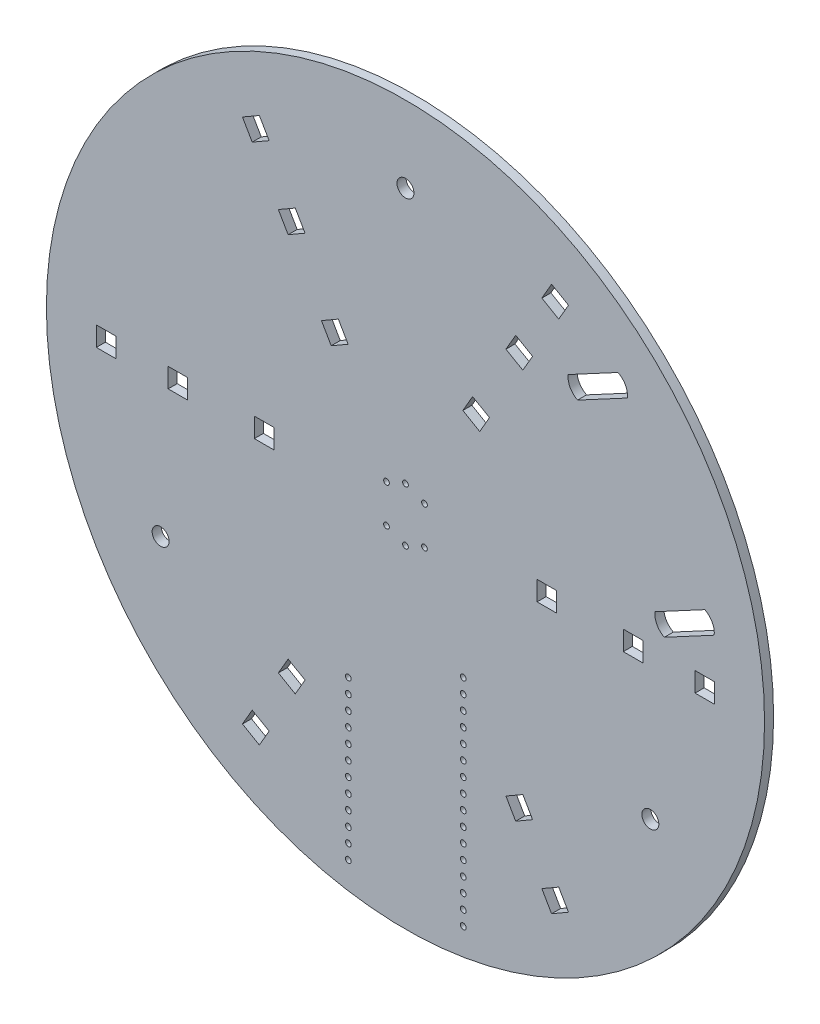
SolidWorks part; units mm, degrees
ref_plane "Front Plane" through (0, 0, 0) normal (0, 0, 1) x (1, 0, 0)
ref_plane "Top Plane" through (0, 0, 0) normal (0, 1, 0) x (1, 0, 0)
ref_plane "Right Plane" through (0, 0, 0) normal (1, 0, 0) x (0, 0, -1)
sketch "Sketch1" plane through (0, 0, 0) normal (0, 0, 1) x (1, 0, 0)
  circle A0 centre (0, 0) radius 63.5
  dimension "D1" = 127
extrude "Boss-Extrude1" add sketch "Sketch1" along normal blind 1.6
sketch "Sketch2" plane through (0, 0, 0) normal (0, 0, -1) x (-1, 0, 0)
  circle A0 centre (0, 0) radius 50
  circle A1 centre (0, 50) radius 1.5
  circle A2 centre (43.3013, -25) radius 1.5
  circle A3 centre (-43.3013, -25) radius 1.5
  point P11 (0, 0)
  dimension "D1" = 100
  dimension "D2" = 3
  dimension "D3" = 3
sketch "Sketch3" plane through (0, 0, 0) normal (0, 0, -1) x (-1, 0, 0)
  circle A0 centre (-34.0063, 36.6548) radius 1.75
  circle A1 centre (-49.3547, 8.0073) radius 1.75
  circle A2 centre (0, 0) radius 63.5 construction
  dimension "D1" = 3.5
  dimension "D2" = 3.5
  dimension "D3" = 32.5
  dimension "D4" = 50
  dimension "D5" = 50
extrude "Cut-Extrude4" cut sketch "Sketch3" against normal blind 1.6
extrude "Cut-Extrude5" cut sketch "Sketch2" against normal blind 1.6 contours A1 | A3 | A2
sketch "Sketch4" plane through (0, 0, 0) normal (0, 0, -1) x (-1, 0, 0)
  line L0 (-34.8328, 35.1122) -> (-48.5282, 9.5498) construction
  line L2 (-52.9355, 11.9111) -> (-44.1209, 7.1886)
  line L3 (-54.5884, 8.826) -> (-45.7738, 4.1034)
  line L6 (-39.2401, 37.4735) -> (-30.4255, 32.7509)
  line L7 (-37.5872, 40.5586) -> (-28.7726, 35.836)
  arc A1 (-45.7738, 4.1034) -> (-44.1209, 7.1886) centre (-47.151, 6.8266) ccw
  circle A2 centre (-34.0063, 36.6548) radius 1.75 construction
  arc A3 (-30.4255, 32.7509) -> (-28.7726, 35.836) centre (-31.8027, 35.4741) ccw
  arc A4 (-39.2401, 37.4735) -> (-37.5872, 40.5586) centre (-36.21, 37.8354) cw
  arc A5 (-54.5884, 8.826) -> (-52.9355, 11.9111) centre (-51.5583, 9.1879) cw
  dimension "D3" = 5
extrude "Cut-Extrude6" cut sketch "Sketch4" against normal blind 10 contours L2 A1 L3 A5 | L6 A3 L7 A4
sketch "Sketch5" plane through (0, 0, 0) normal (0, 0, -1) x (-1, 0, 0)
  line L1 (51.215, 1.725) -> (54.665, -1.725) construction
  line L2 (0, -25) -> (0, 0) construction
  line L3 (51.215, -1.725) -> (54.665, 1.725) construction
  line L4 (-14.8564, 22.282) -> (-11.8686, 24.007)
  line L5 (-23.275, -1.725) -> (-26.725, -1.725)
  line L6 (-23.275, -1.725) -> (-23.275, 1.725)
  line L7 (-23.275, 1.725) -> (-26.725, 1.725)
  line L8 (-26.725, -1.725) -> (-26.725, 1.725)
  line L9 (-23.275, -1.725) -> (-26.725, 1.725) construction
  line L10 (-23.275, 1.725) -> (-26.725, -1.725) construction
  line L11 (-38.515, -1.725) -> (-41.965, -1.725)
  line L12 (-38.515, -1.725) -> (-38.515, 1.725)
  line L13 (-38.515, 1.725) -> (-41.965, 1.725)
  line L14 (-41.965, -1.725) -> (-41.965, 1.725)
  line L15 (-38.515, -1.725) -> (-41.965, 1.725) construction
  line L16 (-38.515, 1.725) -> (-41.965, -1.725) construction
  line L17 (-51.215, -1.725) -> (-54.665, -1.725)
  line L18 (-51.215, -1.725) -> (-51.215, 1.725)
  line L19 (-51.215, 1.725) -> (-54.665, 1.725)
  line L20 (-54.665, -1.725) -> (-54.665, 1.725)
  line L21 (-51.215, -1.725) -> (-54.665, 1.725) construction
  line L22 (-51.215, 1.725) -> (-54.665, -1.725) construction
  line L23 (-10.1436, 21.0192) -> (-11.8686, 24.007)
  line L24 (-13.1314, 19.2942) -> (-14.8564, 22.282)
  line L25 (-13.1314, 19.2942) -> (-10.1436, 21.0192)
  line L26 (-22.4764, 35.4803) -> (-19.4886, 37.2053)
  line L27 (-17.7636, 34.2175) -> (-19.4886, 37.2053)
  line L28 (-20.7514, 32.4925) -> (-17.7636, 34.2175)
  line L29 (-20.7514, 32.4925) -> (-22.4764, 35.4803)
  line L30 (-28.8264, 46.4788) -> (-25.8386, 48.2038)
  line L31 (-27.1014, 43.491) -> (-28.8264, 46.4788)
  line L32 (-24.1136, 45.216) -> (-25.8386, 48.2038)
  line L33 (-27.1014, 43.491) -> (-24.1136, 45.216)
  line L34 (11.8686, 24.007) -> (14.8564, 22.282)
  line L35 (13.1314, 19.2942) -> (14.8564, 22.282)
  line L36 (10.1436, 21.0192) -> (11.8686, 24.007)
  line L37 (10.1436, 21.0192) -> (13.1314, 19.2942)
  line L38 (19.4886, 37.2053) -> (22.4764, 35.4803)
  line L39 (20.7514, 32.4925) -> (22.4764, 35.4803)
  line L40 (17.7636, 34.2175) -> (20.7514, 32.4925)
  line L41 (17.7636, 34.2175) -> (19.4886, 37.2053)
  line L42 (25.8386, 48.2038) -> (28.8264, 46.4788)
  line L43 (24.1136, 45.216) -> (25.8386, 48.2038)
  line L44 (27.1014, 43.491) -> (28.8264, 46.4788)
  line L45 (24.1136, 45.216) -> (27.1014, 43.491)
  line L46 (26.725, 1.725) -> (26.725, -1.725)
  line L47 (23.275, -1.725) -> (26.725, -1.725)
  line L48 (23.275, 1.725) -> (26.725, 1.725)
  line L49 (23.275, 1.725) -> (23.275, -1.725)
  line L50 (41.965, 1.725) -> (41.965, -1.725)
  line L51 (38.515, -1.725) -> (41.965, -1.725)
  line L52 (38.515, 1.725) -> (38.515, -1.725)
  line L53 (38.515, 1.725) -> (41.965, 1.725)
  line L54 (54.665, 1.725) -> (54.665, -1.725)
  line L55 (51.215, 1.725) -> (54.665, 1.725)
  line L56 (51.215, -1.725) -> (54.665, -1.725)
  line L57 (51.215, 1.725) -> (51.215, -1.725)
  line L62 (22.4764, -35.4803) -> (19.4886, -37.2053)
  line L63 (17.7636, -34.2175) -> (19.4886, -37.2053)
  line L64 (20.7514, -32.4925) -> (17.7636, -34.2175)
  line L65 (20.7514, -32.4925) -> (22.4764, -35.4803)
  line L66 (28.8264, -46.4788) -> (25.8386, -48.2038)
  line L67 (27.1014, -43.491) -> (28.8264, -46.4788)
  line L68 (24.1136, -45.216) -> (25.8386, -48.2038)
  line L69 (27.1014, -43.491) -> (24.1136, -45.216)
  line L74 (-19.4886, -37.2053) -> (-22.4764, -35.4803)
  line L75 (-20.7514, -32.4925) -> (-22.4764, -35.4803)
  line L76 (-17.7636, -34.2175) -> (-20.7514, -32.4925)
  line L77 (-17.7636, -34.2175) -> (-19.4886, -37.2053)
  line L78 (-25.8386, -48.2038) -> (-28.8264, -46.4788)
  line L79 (-24.1136, -45.216) -> (-25.8386, -48.2038)
  line L80 (-27.1014, -43.491) -> (-28.8264, -46.4788)
  line L81 (-24.1136, -45.216) -> (-27.1014, -43.491)
  line L83 (26.6205, -46.108) -> (27.7715, -44.6516) construction
  line L89 (-28.8264, 46.4788) -> (-24.1136, 45.216) construction
  line L90 (-27.1014, 43.491) -> (-25.8386, 48.2038) construction
  line L91 (-22.4764, 35.4803) -> (-17.7636, 34.2175) construction
  line L92 (-19.4886, 37.2053) -> (-20.7514, 32.4925) construction
  line L93 (-14.8564, 22.282) -> (-10.1436, 21.0192) construction
  line L94 (-11.8686, 24.007) -> (-13.1314, 19.2942) construction
  line L95 (41.965, 1.725) -> (38.515, -1.725) construction
  line L96 (38.515, 1.725) -> (41.965, -1.725) construction
  line L97 (23.275, 1.725) -> (26.725, -1.725) construction
  line L98 (26.725, 1.725) -> (23.275, -1.725) construction
  line L99 (19.4886, 37.2053) -> (20.7514, 32.4925) construction
  line L100 (22.4764, 35.4803) -> (17.7636, 34.2175) construction
  line L101 (25.8386, 48.2038) -> (27.1014, 43.491) construction
  line L102 (24.1136, 45.216) -> (28.8264, 46.4788) construction
  line L103 (11.8686, 24.007) -> (13.1314, 19.2942) construction
  line L104 (10.1436, 21.0192) -> (14.8564, 22.282) construction
  line L109 (-20.7514, -32.4925) -> (-19.4886, -37.2053) construction
  line L110 (-22.4764, -35.4803) -> (-17.7636, -34.2175) construction
  line L111 (-27.1014, -43.491) -> (-25.8386, -48.2038) construction
  line L112 (-28.8264, -46.4788) -> (-24.1136, -45.216) construction
  line L115 (20.7514, -32.4925) -> (19.4886, -37.2053) construction
  line L116 (17.7636, -34.2175) -> (22.4764, -35.4803) construction
  line L117 (27.1014, -43.491) -> (25.8386, -48.2038) construction
  line L118 (24.1136, -45.216) -> (28.8264, -46.4788) construction
  line L119 (-11.8686, -24.007) -> (-14.8564, -22.282) [skipped]
  line L120 (-13.1314, -19.2942) -> (-14.8564, -22.282) [skipped]
  line L121 (-10.1436, -21.0192) -> (-10.4712, -21.5867) [skipped]
  line L122 (-10.1436, -21.0192) -> (-10.5669, -20.7749) [skipped]
  line L123 (10.1436, -21.0192) -> (11.8686, -24.007) [skipped]
  line L124 (14.8564, -22.282) -> (13.3625, -23.1445) [skipped]
  line L125 (13.1314, -19.2942) -> (11.6375, -20.1567) [skipped]
  line L126 (13.1314, -19.2942) -> (14.8564, -22.282) [skipped]
  circle A7 centre (-10.2194, -19.8355) radius 0.508
  circle A8 centre (-10.2194, -22.3755) radius 0.508
  circle A9 centre (-10.2194, -24.9155) radius 0.508
  circle A10 centre (-10.2194, -27.4555) radius 0.508
  circle A11 centre (-10.2194, -29.9955) radius 0.508
  circle A12 centre (-10.2194, -32.5355) radius 0.508
  circle A13 centre (-10.2194, -35.0755) radius 0.508
  circle A14 centre (-10.2194, -37.6155) radius 0.508
  circle A15 centre (-10.2194, -40.1555) radius 0.508
  circle A16 centre (-10.2194, -42.6955) radius 0.508
  circle A17 centre (-10.2194, -45.2355) radius 0.508
  circle A18 centre (-10.2194, -47.7755) radius 0.508
  circle A19 centre (-10.2194, -50.3155) radius 0.508
  circle A20 centre (-10.2194, -52.8555) radius 0.508
  circle A21 centre (-10.2194, -55.3955) radius 0.508
  circle A22 centre (-10.2194, -57.9355) radius 0.508
  circle A23 centre (10.1006, -57.9355) radius 0.508
  circle A24 centre (10.1006, -55.3955) radius 0.508
  circle A25 centre (10.1006, -52.8555) radius 0.508
  circle A26 centre (10.1006, -50.3155) radius 0.508
  circle A27 centre (10.1006, -47.7755) radius 0.508
  circle A28 centre (10.1006, -45.2355) radius 0.508
  circle A29 centre (10.1006, -42.6955) radius 0.508
  circle A30 centre (10.1006, -40.1555) radius 0.508
  circle A31 centre (10.1006, -37.6155) radius 0.508
  circle A32 centre (10.1006, -29.9955) radius 0.508
  circle A33 centre (10.1006, -32.5355) radius 0.508
  circle A34 centre (10.1006, -35.0755) radius 0.508
  point P4 (-25, 0)
  point P11 (-40.24, 0)
  point P89 (0, 0)
  dimension "D10" = 25
  dimension "D2" = 15.24
  dimension "D3" = 25
  dimension "D4" = 2.54
  dimension "D5" = 38.1
  dimension "D7" = 22.7185
  dimension "D8" = 20.32
  dimension "D9" = 19.8355
  dimension "D11" = 0
  dimension "D15" = 15
  dimension "D16" = 2
  dimension "D6" = 6
extrude "Cut-Extrude7" cut sketch "Sketch5" against normal blind 10
sketch "Sketch6" plane through (0, 0, 0) normal (0, 0, -1) x (-1, 0, 0)
  circle A2 centre (0, 4.75) radius 0.5
  circle A3 centre (-3.3588, 3.3588) radius 0.5
  circle A4 centre (3.3588, 3.3588) radius 0.5
  circle A5 centre (3.3588, -3.3588) radius 0.5
  circle A6 centre (0, -4.75) radius 0.5
  circle A7 centre (-3.3588, -3.3588) radius 0.5
  dimension "D2" = 1
extrude "Cut-Extrude8" cut sketch "Sketch6" against normal blind 10
sketch "Sketch7" plane through (0, 0, 0) normal (0, 0, -1) x (-1, 0, 0)
  line L0 (-54.665, 1.725) -> (-51.215, -1.725) construction
  line L1 (-51.215, -1.725) -> (-51.215, 1.725) construction
  line L2 (-51.215, 1.725) -> (-54.665, -1.725) construction
  line L3 (-41.965, 1.725) -> (-38.515, -1.725) construction
  line L4 (-38.515, -1.725) -> (-38.515, 1.725) construction
  line L5 (-38.515, 1.725) -> (-41.965, -1.725) construction
  line L6 (-26.725, 1.725) -> (-23.275, -1.725) construction
  line L7 (-23.275, -1.725) -> (-23.275, 1.725) construction
  line L8 (-23.275, 1.725) -> (-26.725, -1.725) construction
  line L9 (-24.1136, 45.216) -> (-28.8264, 46.4788) construction
  line L10 (-25.8386, 48.2038) -> (-27.1014, 43.491) construction
  line L11 (-19.4886, 37.2053) -> (-20.7514, 32.4925) construction
  line L12 (-17.7636, 34.2175) -> (-22.4764, 35.4803) construction
  line L13 (-11.8686, 24.007) -> (-13.1314, 19.2942) construction
  line L14 (-10.1436, 21.0192) -> (-14.8564, 22.282) construction
  line L15 (27.1014, 43.491) -> (25.8386, 48.2038) construction
  line L16 (28.8264, 46.4788) -> (24.1136, 45.216) construction
  line L17 (22.4764, 35.4803) -> (17.7636, 34.2175) construction
  line L18 (20.7514, 32.4925) -> (19.4886, 37.2053) construction
  line L19 (14.8564, 22.282) -> (10.1436, 21.0192) construction
  line L20 (13.1314, 19.2942) -> (11.8686, 24.007) construction
  line L21 (51.215, -1.725) -> (54.665, 1.725) construction
  line L22 (54.665, -1.725) -> (51.215, 1.725) construction
  line L23 (41.965, -1.725) -> (38.515, 1.725) construction
  line L24 (38.515, -1.725) -> (41.965, 1.725) construction
  line L25 (26.725, -1.725) -> (23.275, 1.725) construction
  line L26 (23.275, -1.725) -> (26.725, 1.725) construction
  line L27 (24.1136, -45.216) -> (28.8264, -46.4788) construction
  line L28 (25.8386, -48.2038) -> (27.1014, -43.491) construction
  line L29 (19.4886, -37.2053) -> (20.7514, -32.4925) construction
  line L30 (17.7636, -34.2175) -> (22.4764, -35.4803) construction
  line L33 (-27.1014, -43.491) -> (-25.8386, -48.2038) construction
  line L34 (-28.8264, -46.4788) -> (-24.1136, -45.216) construction
  line L35 (-22.4764, -35.4803) -> (-17.7636, -34.2175) construction
  line L36 (-20.7514, -32.4925) -> (-19.4886, -37.2053) construction
  line L39 (-12.5, -21.6506) -> (-10.1436, -21.0192) construction
  line L40 (-12.5, -21.6506) -> (-11.8686, -24.007) construction
  line L41 (10.1436, -21.0192) -> (12.5, -21.6506) construction
  line L42 (12.5, -21.6506) -> (13.1314, -19.2942) construction
  point P87 (0, 0)
  dimension "D1" = 6
